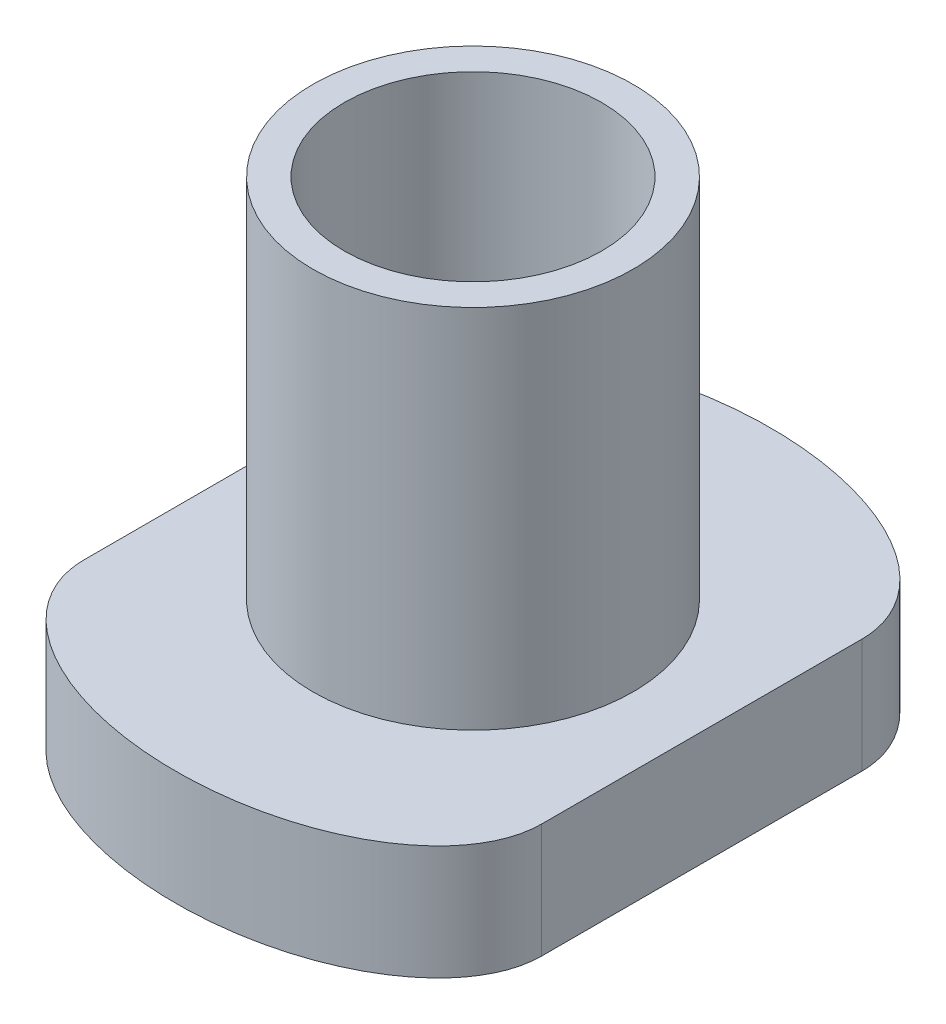
SolidWorks part; units mm, degrees
material "Plain Carbon Steel"
ref_plane "Front Plane" through (0, 0, 0) normal (0, 0, 1) x (1, 0, 0)
ref_plane "Top Plane" through (0, 0, 0) normal (0, 1, 0) x (1, 0, 0)
ref_plane "Right Plane" through (0, 0, 0) normal (1, 0, 0) x (0, 0, -1)
sketch "Sketch1" plane through (0, 0, 0) normal (0, 1, 0) x (1, 0, 0)
  line L0 (0, 26) -> (40, 26) construction
  line L5 (20, 52) -> (20, 0) construction
  line L7 (0, 40) -> (0, 12)
  line L8 (40, 40) -> (40, 12)
  ellipse E0 centre (20, 40) end of major axis (0, 40) minor radius 12 (0, 40) -> (40, 40) cw
  ellipse E1 centre (20, 12) end of major axis (40, 12) minor radius 12 (40, 12) -> (0, 12) cw
extrude "Boss-Extrude1" add sketch "Sketch1" along normal blind 10 contours E0 L8 E1 L7
sketch "Sketch2" plane through (0, 10, 0) normal (0, 1, 0) x (1, 0, 0)
  line L0 (20, 52) -> (20, 0) construction
  circle A0 centre (20, 26) radius 14
  ellipse E0 centre (20, 40) end of major axis (0, 40) minor radius 12 (40, 40) -> (0, 40) ccw construction
  ellipse E1 centre (20, 12) end of major axis (40, 12) minor radius 12 (0, 12) -> (40, 12) ccw construction
  dimension "D1" = 28
extrude "Boss-Extrude2" add sketch "Sketch2" along normal blind 32 contours A0
sketch "Sketch3" plane through (0, 42, 0) normal (0, 1, 0) x (1, 0, 0)
  line L0 (20, 40) -> (20, 12) construction
  circle A0 centre (20, 26) radius 14 construction
  circle A1 centre (20, 26) radius 14 construction
  circle A2 centre (20, 26) radius 11.25
  dimension "D1" = 22.5
extrude "Cut-Extrude1" cut sketch "Sketch3" against normal through all
